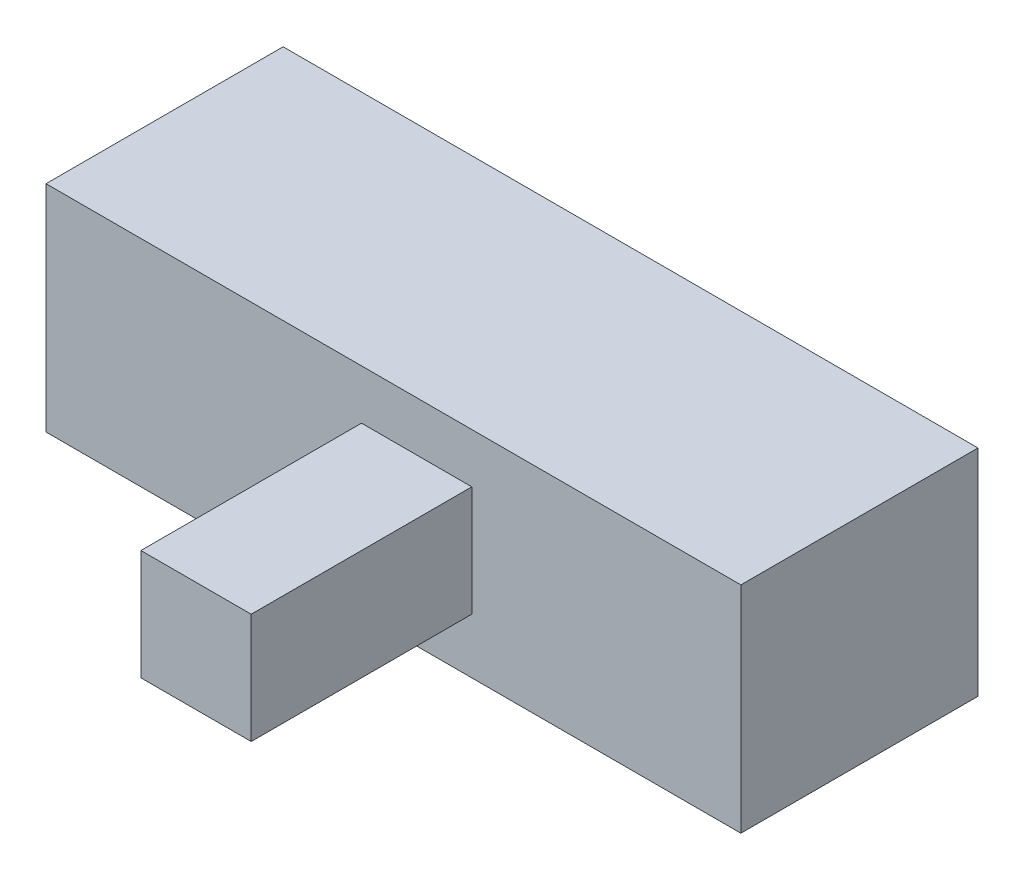
SolidWorks part; units mm, degrees
ref_plane "Front Plane" through (0, 0, 0) normal (0, 0, 1) x (1, 0, 0)
ref_plane "Top Plane" through (0, 0, 0) normal (0, 1, 0) x (1, 0, 0)
ref_plane "Right Plane" through (0, 0, 0) normal (1, 0, 0) x (0, 0, -1)
sketch "Sketch1" plane through (0, 0, 0) normal (0, 0, 1) x (1, 0, 0)
  line L1 (0, 0) -> (12.6, 0)
  line L2 (0, 0) -> (0, 3.9)
  line L3 (0, 3.9) -> (12.6, 3.9)
  line L4 (12.6, 0) -> (12.6, 3.9)
  dimension "D1" = 3.9
  dimension "D2" = 12.6
extrude "Boss-Extrude1" add sketch "Sketch1" along normal blind 4.3 contours L1 L4 L3 L2
sketch "Sketch2" plane through (0, 0, 4.3) normal (0, 0, 1) x (1, 0, 0)
  line L0 (0, 0) -> (12.6, 0) construction
  line L1 (5.721, 3) -> (7.721, 3)
  line L2 (5.721, 3) -> (5.721, 1)
  line L3 (5.721, 1) -> (7.721, 1)
  line L4 (7.721, 3) -> (7.721, 1)
  dimension "D1" = 2
  dimension "D2" = 2
  dimension "D3" = 1
extrude "Boss-Extrude2" add sketch "Sketch2" along normal blind 4
